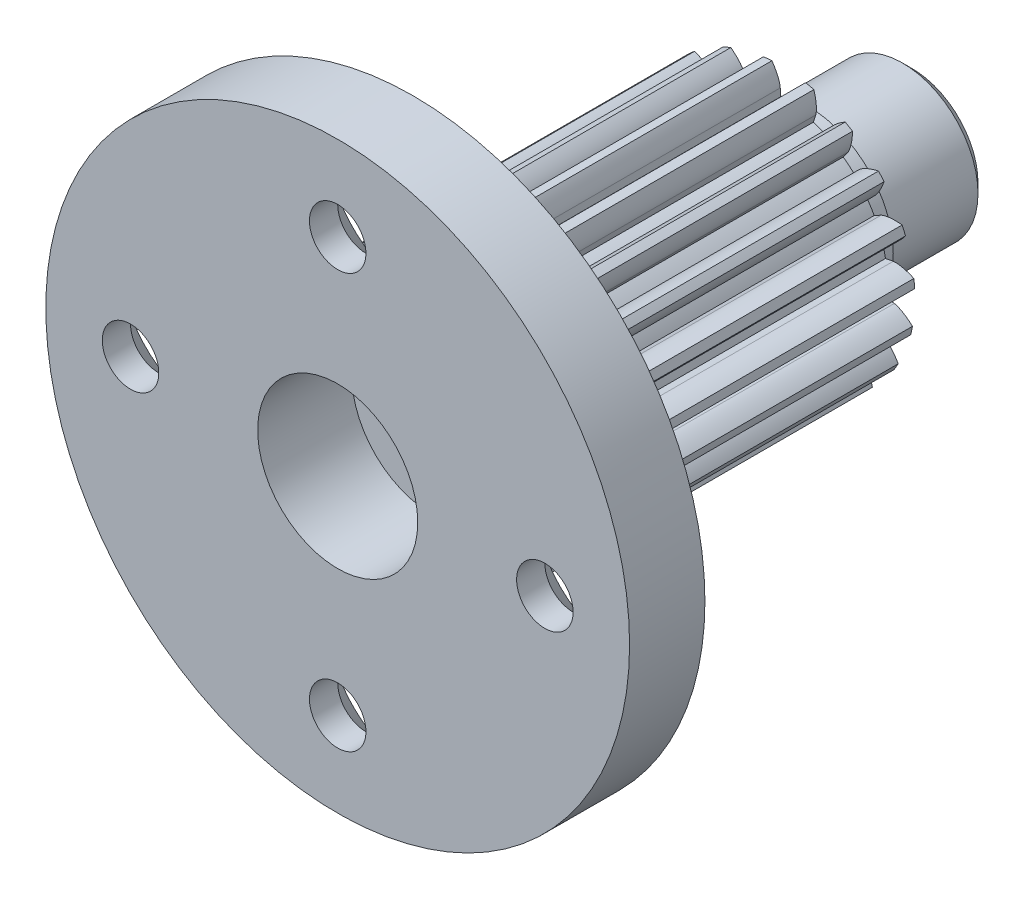
SolidWorks part; units mm, degrees
ref_plane "Front Plane" through (0, 0, 0) normal (0, 0, 1) x (1, 0, 0)
ref_plane "Top Plane" through (0, 0, 0) normal (0, 1, 0) x (1, 0, 0)
ref_plane "Right Plane" through (0, 0, 0) normal (1, 0, 0) x (0, 0, -1)
sketch "Sketch1" plane through (0, 0, 0) normal (0, 0, 1) x (1, 0, 0)
  circle A0 centre (0, 0) radius 7.15
  dimension "D1" = 14.3
extrude "Boss-Extrude1" add sketch "Sketch1" along normal mid plane 19.5
sketch "Sketch2" plane through (0, 0, 0) normal (0, 0, 1) x (1, 0, 0)
  line L0 (0, 0) -> (6.108, 0) construction
  line L1 (0, 0) -> (6.4868, -0.4134) construction
  line L2 (0, 0) -> (6.0586, -0.7753) construction
  line L3 (6.108, 0) -> (5.6875, 0)
  line L4 (6.0586, -0.7753) -> (5.6415, -0.7219)
  circle A0 centre (0, 0) radius 6.5 construction
  circle A1 centre (0, 0) radius 6.108 construction
  circle A2 centre (0, 0) radius 5.6875
  circle A3 centre (0, 0) radius 7.15 construction
  circle A4 centre (0, 0) radius 7.15
  spline S0 degree 4 poles (6.108, 0) (6.1101, 0) (6.1159, 0.0002) (6.134, 0.0014) (6.1696, 0.0053) (6.2133, 0.0126) (6.2634, 0.0233) (6.3114, 0.0354) (6.3523, 0.0469) (6.393, 0.0594) (6.4333, 0.0728) (6.482, 0.0901) (6.54, 0.1123) (6.6073, 0.1406) (6.683, 0.1752) (6.7595, 0.2132) (6.8341, 0.2528) (6.9087, 0.2955) (6.9803, 0.3385) (7.0538, 0.3858) (7.1213, 0.4308) (7.1958, 0.4841) (7.2556, 0.5279) (7.3334, 0.5886) (7.379, 0.6253) (7.4319, 0.6694) (7.4552, 0.6895) (7.4695, 0.7018) knots 0 0 0 0 0 0.005377 0.015084 0.04661 0.092111 0.119476 0.146842 0.174209 0.201575 0.228941 0.256307 0.307035 0.361767 0.4165 0.471232 0.525964 0.580697 0.635429 0.690161 0.744894 0.799626 0.854358 0.909091 0.954545 1 1 1 1 1 construction
  spline S1 degree 4 poles (6.108, 0) (6.1101, 0) (6.1159, 0.0002) (6.134, 0.0014) (6.1696, 0.0053) (6.2133, 0.0126) (6.2634, 0.0233) (6.3114, 0.0354) (6.3523, 0.0469) (6.393, 0.0594) (6.4333, 0.0728) (6.482, 0.0901) (6.54, 0.1123) (6.6073, 0.1406) (6.683, 0.1752) (6.7595, 0.2132) (6.8341, 0.2528) (6.9087, 0.2955) (6.9803, 0.3385) (7.0538, 0.3858) (7.1213, 0.4308) (7.1958, 0.4841) (7.2556, 0.5279) (7.3165, 0.5754) (7.346, 0.5989) (7.3611, 0.6111) knots 0 0 0 0 0 0.005377 0.015084 0.04661 0.092111 0.119476 0.146842 0.174209 0.201575 0.228941 0.256307 0.307035 0.361767 0.4165 0.471232 0.525964 0.580697 0.635429 0.690161 0.744894 0.799626 0.854358 0.909091 0.909091 0.909091 0.909091 0.909091
  spline S2 degree 4 poles (6.0586, -0.7753) (6.0607, -0.7756) (6.0665, -0.7765) (6.0842, -0.7799) (6.119, -0.7884) (6.1615, -0.8011) (6.2097, -0.8181) (6.2559, -0.8362) (6.295, -0.8528) (6.3338, -0.8704) (6.3721, -0.8888) (6.4181, -0.9121) (6.4728, -0.9415) (6.536, -0.9781) (6.6067, -1.022) (6.6777, -1.0694) (6.7467, -1.1182) (6.8153, -1.17) (6.8809, -1.2218) (6.9478, -1.2781) (7.009, -1.3312) (7.0761, -1.3935) (7.1299, -1.4445) (7.1994, -1.5146) (7.2399, -1.5569) (7.2868, -1.6073) (7.3074, -1.6302) (7.32, -1.6442) knots 0 0 0 0 0 0.005377 0.015084 0.04661 0.092111 0.119476 0.146842 0.174209 0.201575 0.228941 0.256307 0.307035 0.361767 0.4165 0.471232 0.525964 0.580697 0.635429 0.690161 0.744894 0.799626 0.854358 0.909091 0.954545 1 1 1 1 1 construction
  spline S3 degree 4 poles (6.0586, -0.7753) (6.0607, -0.7756) (6.0665, -0.7765) (6.0842, -0.7799) (6.119, -0.7884) (6.1615, -0.8011) (6.2097, -0.8181) (6.2559, -0.8362) (6.295, -0.8528) (6.3338, -0.8704) (6.3721, -0.8888) (6.4181, -0.9121) (6.4728, -0.9415) (6.536, -0.9781) (6.6067, -1.022) (6.6777, -1.0694) (6.7467, -1.1182) (6.8153, -1.17) (6.8809, -1.2218) (6.9478, -1.2781) (7.009, -1.3312) (7.0761, -1.3935) (7.1299, -1.4445) (7.1843, -1.4994) (7.2106, -1.5265) (7.224, -1.5404) knots 0 0 0 0 0 0.005377 0.015084 0.04661 0.092111 0.119476 0.146842 0.174209 0.201575 0.228941 0.256307 0.307035 0.361767 0.4165 0.471232 0.525964 0.580697 0.635429 0.690161 0.744894 0.799626 0.854358 0.909091 0.909091 0.909091 0.909091 0.909091
  dimension "D1" = 13
  dimension "D2" = 12.216
  dimension "D3" = 11.375
  dimension "D4" = 3.646
  dimension "D5" = 3.646
extrude "Cut-Extrude1" cut sketch "Sketch2" against normal through all both and the other way through all contours A2 S3 A4 S1
pattern_circular "CirPattern2" count 20 over 360 about axis through (0, 0, -9.75) along (0, 0, 1) of "Cut-Extrude1"
sketch "Sketch3" plane through (0, 0, 0) normal (0, 1, 0) x (1, 0, 0)
  line L0 (0, 9.75) -> (0, 20.841) construction
  line L1 (0, 20.841) -> (0, -26.4333) construction
  line L2 (0, 16.75) -> (-4, 16.75)
  line L3 (-4, 16.75) -> (-4, 11.25)
  line L4 (-4, 11.25) -> (-4.5, 11.25)
  line L6 (-4.5, 11.25) -> (-4.5, 9.75)
  line L9 (0, 9.75) -> (-4.5, 9.75)
  line L10 (-0.442, -9.75) -> (0, -9.75) construction
  line L11 (0, -9.75) -> (-15.5, -9.75)
  line L12 (-15.5, -9.75) -> (-15.5, -13.75)
  line L13 (-15.5, -13.75) -> (0, -13.75)
  line L14 (0, 16.75) -> (0, -13.75)
  line L15 (0, 9.75) -> (-0.442, 9.75) construction
  point P7 (0, -9.75)
  point P14 (0, 9.75)
  point P23 (0, 0)
  dimension "D1" = 4
  dimension "D2" = 5.5
  dimension "D3" = 1.5
  dimension "D4" = 0.5
  dimension "D5" = 4
  dimension "D6" = 15.5
revolve "Revolve1" add sketch "Sketch3" angle 360 about L0
chamfer "Chamfer1" distance 0.5 angle 45 1 edges at (4.5, 0, -9.75)
chamfer "Chamfer2" distance 0.5 angle 45 1 edges at (4, 0, -16.75)
sketch "Sketch4" plane through (0, 0, 13.75) normal (0, 0, 1) x (1, 0, 0)
  circle A0 centre (0, 0) radius 2.5
  dimension "D1" = 5
extrude "Cut-Extrude2" cut sketch "Sketch4" against normal through all
sketch "Sketch5" plane through (0, 0, 13.75) normal (0, 0, 1) x (1, 0, 0)
  circle A0 centre (0, 0) radius 4.25
  dimension "D1" = 8.5
extrude "Cut-Extrude3" cut sketch "Sketch5" against normal blind 5
sketch "Sketch6" plane through (0, 0, 9.75) normal (0, 0, -1) x (-1, 0, 0)
  circle A0 centre (0, 0) radius 11 construction
  circle A1 centre (0, 11) radius 1.5
  circle A2 centre (11, 0) radius 1.5
  circle A3 centre (0, -11) radius 1.5
  circle A4 centre (-11, 0) radius 1.5
  point P5 (0, 0)
  point P14 (0, 0)
  dimension "D1" = 22
  dimension "D2" = 3
  dimension "D3" = 4
extrude "Cut-Extrude4" cut sketch "Sketch6" against normal through all
sketch "Sketch7" plane through (0, 0, 0) normal (0, 1, 0) x (1, 0, 0)
  line L0 (9.5, -13.75) -> (12.5, -13.75) construction
  line L1 (12.5, -9.75) -> (9.5, -9.75) construction
  line L2 (9.5, -13.75) -> (12.5, -13.75)
  line L3 (12.5, -9.75) -> (9.5, -9.75)
  line L4 (11, -9.75) -> (11, -13.75) construction
  line L5 (11, -9.75) -> (15.5, -9.75)
  line L6 (15.5, -9.75) -> (12.5, -12.25)
  line L7 (12.5, -12.25) -> (11, -12.25)
  line L8 (11, -9.75) -> (11, -12.25)
  dimension "D3" = 1.5
  dimension "D1" = 2.5
  dimension "D2" = 4.5
revolve "Cut-Revolve1" cut sketch "Sketch7" angle 360 about L4
pattern_circular "CirPattern3" count 4 over 360 about axis through (0, 0, 0) along (0, 0, 1) of "Cut-Revolve1"
equation "\"Ns\"= 20"
equation "\"module\"= 0.65"
equation "\"pressure angle\"= 20deg"
equation "\"h_a\"= 1 * \"module\"'addendum"
equation "\"h_b\"= 1.25 * \"module\"'dedendum"
equation "\"clr_tip_root\"= \"h_f\" - \"h_a\"'clearance of gear tooth tip and root"
equation "\"dp_s\"= \"module\" * \"Ns\"'PCD"
equation "\"db_s\"= \"dp_s\" * cos ( \"pressure angle\" )'base CD"
equation "\"D1@Sketch1\"=\"dp_s\" + 2*\"h_a\""
equation "\"fw_s_calc\"= 13mm'face width"
equation "\"D1@Boss-Extrude1\"=\"fw_s_used\""
equation "\"D1@Sketch2\"=\"dp_s\""
equation "\"D2@Sketch2\"= \"db_s\""
equation "\"D3@Sketch2\"=\"dp_s\"- 2*\"h_b\""
equation "\"alpha_s\"= sqr ( \"dp_s\" ^ 2 - \"db_s\" ^ 2 ) / \"db_s\" * 180 / pi - \"pressure angle\""
equation "\"D4@Sketch2\"= 360 / ( 4 * \"Ns\" ) - \"alpha_s\""
equation "\"beta_s\"= ( 360 / ( 4 * \"Ns\" ) - \"alpha_s\" ) * 2"
equation "\"D5@Sketch2\"= 360 / ( 4 * \"Ns\" ) - \"alpha_s\""
equation "\"D1@CirPattern2\"=\"Ns\""
equation "\"Np\"= 40"
equation "\"dp_p\"= \"module\" * \"Np\"'PCD"
equation "\"db_p\"= \"dp_p\" * cos ( \"pressure angle\" )'base CD"
equation "\"fw_p\"= \"fw_r\""
equation "\"alpha_p\"= sqr ( \"dp_p\" ^ 2 - \"db_p\" ^ 2 ) / \"db_p\" * 180 / pi - \"pressure angle\""
equation "\"beta_p\"= ( 360 / ( 4 * \"Np\" ) - \"alpha_p\" ) * 2"
equation "\"Nr\"= \"Ns\" + 2 * \"Np\"'num teeth"
equation "\"pressure_angle\"= 20deg"
equation "\"h_f\"= 1.25 * \"module\"'dedendum"
equation "\"dp_r\"= \"module\" * \"Nr\"'PCD"
equation "\"db_r\"= \"dp_r\" * cos ( \"pressure_angle\" )'base CD"
equation "\"fw_r\"= 11.5mm'face width"
equation "\"alpha_r\"= sqr ( \"dp_r\" ^ 2 - \"db_r\" ^ 2 ) / \"db_r\" * 180 / pi - \"pressure_angle\""
equation "\"beta_r\"= ( 360 / ( 4 * \"Nr\" ) + \"alpha_r\" ) * 2"
equation "\"bearing_ID\"= \"module\" * ( \"Ns\" + \"Np\" ) + 10"
equation "\"bearing_OD\"= 1.18 * \"bearing_ID\" + 8.57"
equation "\"bearing_height\"= 0.09 * \"bearing_ID\" + 4.62"
equation "\"clearance_planet\"=1.5"
equation "\"case_dist\"= \"sec_carrier_thickness\" + \"clearance_planet\" + \"sun_coupler_hub_thickness\" - \"case_mounting_surface_height\""
equation "\"Motor_case_OD_max\"= \"case_mounting_PCD\" + \"case_mounting_hole_allen_socket_dia\" + \"clearance_case_mount_holes_shell_thickness\" * 2"
equation "\"case_mounting_PCD\"= \"motor_case_OD_base\" + \"case_mounting_hole_shift\" * 2"
equation "\"bearing mount thickness\"= \"output_mounting_hole_dia\" * 2"
equation "\"case_mounting_hole_dia\"=3"
equation "\"output_mounting_PCD\"= \"bearing_OD\" + \"bearing mount thickness\""
equation "\"output_mounting_hole_dia\"= 4"
equation "\"clearance_case_mount_holes_shell_thickness\"= 1"
equation "\"motor_case_OD_base\"= \"motor_OD\" + \"clearance_motor_and_case\" * 2 + \"Motor_case_thickness\" * 2"
equation "\"sec_carrier_thickness\"= 5"
equation "\"sun_coupler_hub_thickness\"= 4"
equation "\"clearance_sun_coupler_sec_carrier\"= 1.5"
equation "\"clearance_motor_and_case\"= 2.2"
equation "\"motor_OD\"= 72"
equation "\"Motor_case_thickness\"= 2"
equation "\"Motor_case_ID\"= \"motor_OD\" + \"clearance_motor_and_case\" * 2"
equation "\"case_mounting_hole_shift\"= \"case_mounting_hole_dia\" / 2 - 0.5"
equation "\"output_mounting_nut_wrench_size\"= 7"
equation "\"output_mounting_nut_thickness\"= 3.2"
equation "\"case_mounting_hole_allen_socket_dia\"= 5.5"
equation "\"output_mounting_nut_depth\"= 3"
equation "\"case_mounting_bolt_depth\"= 4.5"
equation "\"ring_radial_thickness\"= 5"
equation "\"ring_OD\"= \"Nr\" * \"module\" + \"ring_radial_thickness\" * 2"
equation "\"ring_to_chamfer_clearance\"= 2"
equation "\"Motor_case_OD_base_to_chamfer\"=5"
equation "\"pattern_offset_from_motor_case_OD_base\"= 3"
equation "\"pattern_bulge_dia\"= 3"
equation "\"pattern_num_bulge\"= 18"
equation "\"pattern_depth\"= 2"
equation "\"motor_height\"= 27"
equation "\"case_mounting_wrench_size\"= 5.5"
equation "\"case_mounting_nut_clearance\"= 2"
equation "\"base_plate_thickness\"= 4"
equation "\"case_mounting_nut_thickness\"= 2.4"
equation "\"case_mounting_surface_height\"= 4"
equation "\"motor_mount_hole_PCD\"= 32"
equation "\"motor_mount_hole_dia\"= 4"
equation "\"motor_mount_hole_num\"= 4"
equation "\"central_hole_offset_from_motor_mount_PCD\"= 5"
equation "\"wire_slot_dist_from_center\"= 30"
equation "\"wire_slot_length\"= 10"
equation "\"wire_slot_radius\"= 4"
equation "\"driver_upper_holes_dist_from_center\"= 23"
equation "\"driver_lower_holes_dist_from_center\"= 15"
equation "\"driver_side_holes_dist_from_center\"= 20"
equation "\"driver_mount_holes_dia\"= 2.5"
equation "\"driver_mount_inserts_OD\"= 3.5"
equation "\"driver_mount_thickness\"= 1.5"
equation "\"driver_mount_height\"= 4"
equation "\"air_flow_hole_offset\"= 3"
equation "\"num_planet\"= 3"
equation "\"planet_pin_bolt_dia\"= 5"
equation "\"planet_pin_socket_head_dia\"= 8.5"
equation "\"carrier_PCD\"= ( \"Np\" + \"Ns\" ) * \"module\""
equation "\"planet_shaft_dia\"= 8"
equation "\"planet_shaft_step_offset\"= 1"
equation "\"carrier_trapezoidal_support_sun_offset\"= 5"
equation "\"carrier_trapezoidal_support_hole_PCD_offset_bearing_ID\"= 4"
equation "\"carrier_trapezoidal_support_hole_dia\"= 3"
equation "\"carrier_trapezoidal_support_hole_socket_head_dia\"= 5.5"
equation "\"carrier_bearing_step_width\"= 1.5"
equation "\"standard_clearance_1_5mm\"=1.5"
equation "\"standard_fillet_1_5mm\"= 1.5"
equation "\"sun_shaft_bearing_OD\"= 16"
equation "\"sun_shaft_bearing_width\"= 4"
equation "\"standard_bearing_insertion_chamfer\"= 0.5"
equation "\"carrier_trapezoidal_support_hole_wrench_size\"= 5.5"
equation "\"planet_pin_bolt_wrench_size\"= 8"
equation "\"planet_bearing_OD\"= 12"
equation "\"planet_bearing_width\"= 3"
equation "\"planet_bore\"= 10"
equation "\"motor_output_hole_PCD\"= 22"
equation "\"motor_output_hole_dia\"= 3"
equation "\"motor_output_hole_num\"= 4"
equation "\"sun_shaft_bearing_ID\"= 8"
equation "\"D1@Sketch3\"=\"sun_shaft_bearing_ID\"/2"
equation "\"D2@Sketch3\"=\"sun_shaft_bearing_width\" + \"standard_clearance_1_5mm\""
equation "\"D3@Sketch3\"=\"standard_clearance_1_5mm\""
equation "\"D4@Sketch3\"=\"standard_clearance_1_5mm\"/3"
equation "\"D5@Sketch3\"=\"sun_coupler_hub_thickness\""
equation "\"sun_hub_dia\"= \"motor_output_hole_PCD\" + \"motor_output_hole_dia\" + \"standard_clearance_1_5mm\" * 4"
equation "\"D6@Sketch3\"=\"sun_hub_dia\"/2"
equation "\"D1@Chamfer2\"=\"standard_bearing_insertion_chamfer\""
equation "\"D1@Chamfer1\"=\"standard_bearing_insertion_chamfer\""
equation "\"sun_central_bolt_dia\"= 5"
equation "\"sun_central_bolt_socket_head_dia\"= 8.5"
equation "\"D1@Sketch4\"=\"sun_central_bolt_dia\""
equation "\"D1@Cut-Extrude3\"=\"sun_central_bolt_dia\""
equation "\"D1@Sketch5\"=\"sun_central_bolt_socket_head_dia\""
equation "\"fw_s_used\"= \"fw_p\" + \"clearance_planet\" + \"sec_carrier_thickness\" + \"standard_clearance_1_5mm\""
equation "\"D1@Sketch6\"=\"motor_output_hole_PCD\""
equation "\"D2@Sketch6\"=\"motor_output_hole_dia\""
equation "\"D3@Sketch6\"=\"motor_output_hole_num\""
equation "\"motor_output_hole_CSK_OD\"= 9'8.96 is exact value"
equation "\"motor_output_hole_CSK_head_height\"= 2.5"
equation "\"D1@Sketch7\"=\"motor_output_hole_CSK_head_height\""
equation "\"D2@Sketch7\"=\"motor_output_hole_CSK_OD\"/2"
equation "\"D3@Sketch7\"=\"motor_output_hole_dia\"/2"
equation "\"D1@CirPattern3\"=\"motor_output_hole_num\""
